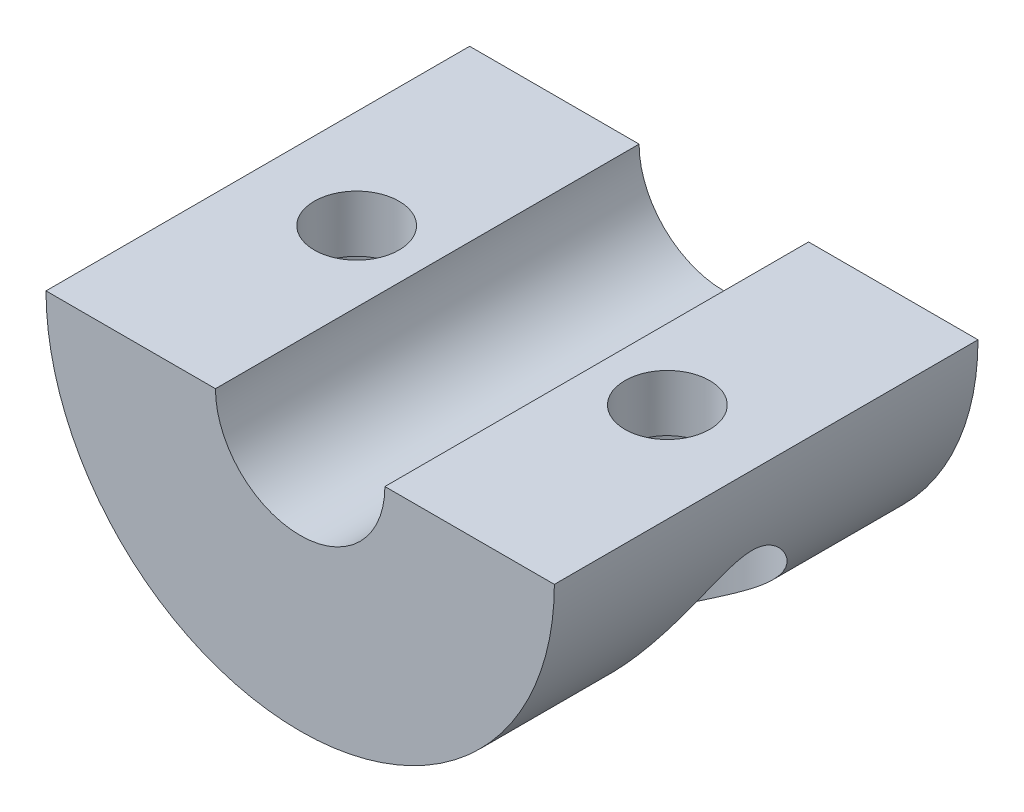
SolidWorks part; units mm, degrees
ref_plane "Спереди" through (0, 0, 0) normal (0, 0, 1) x (1, 0, 0)
ref_plane "Сверху" through (0, 0, 0) normal (0, 1, 0) x (1, 0, 0)
ref_plane "Справа" through (0, 0, 0) normal (1, 0, 0) x (0, 0, -1)
sketch "Sketch1" plane through (0, 0, 0) normal (0, 0, 1) x (1, 0, 0)
  line L0 (-9, 0) -> (9, 0)
  circle A0 centre (0, 0) radius 9
  circle A1 centre (0, 0) radius 3
  dimension "D1" = 6
  dimension "D2" = 6
extrude "Boss-Extrude1" add sketch "Sketch1" along normal blind 15 contours A1 L0 A0
ref_plane "Plane1" through (0, -2, 0) normal (0, 1, 0) x (1, 0, 0)
sketch "Sketch2" plane through (0, -2, 0) normal (0, 1, 0) x (1, 0, 0)
  line L0 (9, -15) -> (9, 0) construction
  line L1 (9, 0) -> (-9, 0) construction
  circle A0 centre (5.5, -7.5) radius 3
  dimension "D1" = 6
  dimension "D2" = 3.5
  dimension "D3" = 7.5
extrude "Cut-Extrude1" cut sketch "Sketch2" against normal blind 15
sketch "Sketch3" plane through (0, -2, 0) normal (0, -1, 0) x (1, 0, 0)
  circle A0 centre (5.5, 7.5) radius 1.5
  dimension "D1" = 3
extrude "Cut-Extrude2" cut sketch "Sketch3" against normal blind 15
mirror "Mirror1" about plane through (0, 0, 0) normal (1, 0, 0) of "Cut-Extrude2", "Cut-Extrude1"
